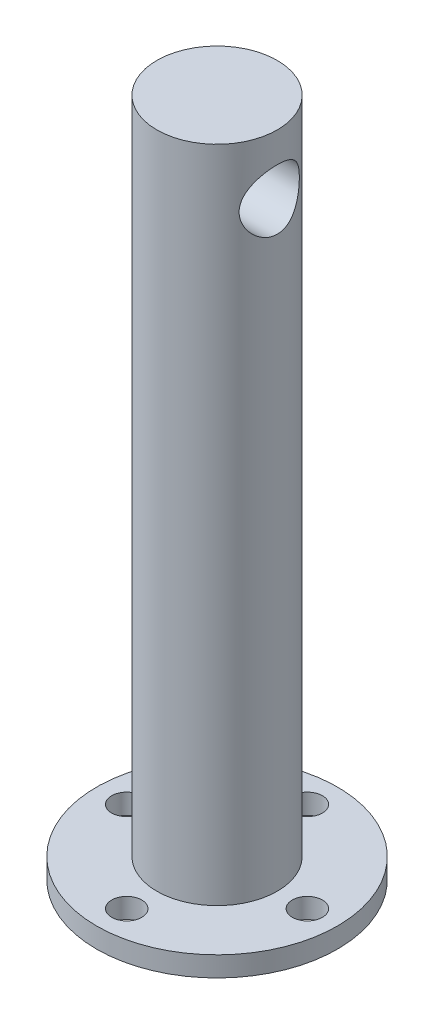
SolidWorks part; units mm, degrees
ref_plane "Front Plane" through (0, 0, 0) normal (0, 0, 1) x (1, 0, 0)
ref_plane "Top Plane" through (0, 0, 0) normal (0, 1, 0) x (1, 0, 0)
ref_plane "Right Plane" through (0, 0, 0) normal (1, 0, 0) x (0, 0, -1)
sketch "Sketch1" plane through (0, 0, 0) normal (0, 1, 0) x (1, 0, 0)
  circle A0 centre (0, 0) radius 30
  dimension "D1" = 60
extrude "Boss-Extrude1" add sketch "Sketch1" along normal blind 5
sketch "Sketch2" plane through (0, 5, 0) normal (0, 1, 0) x (1, 0, 0)
  circle A1 centre (0, 22.5) radius 3.75
  circle A2 centre (22.5, 0) radius 3.75
  circle A3 centre (0, -22.5) radius 3.75
  circle A4 centre (-22.5, 0) radius 3.75
  point P12 (0, 0)
  dimension "D1" = 7.5
  dimension "D2" = 22.5
  dimension "D3" = 4
extrude "Cut-Extrude1" cut sketch "Sketch2" against normal blind 5
sketch "Sketch3" plane through (0, 5, 0) normal (0, 1, 0) x (1, 0, 0)
  circle A0 centre (0, 0) radius 15
  dimension "D1" = 30
extrude "Boss-Extrude2" add sketch "Sketch3" along normal blind 164.27
ref_plane "Plane1" through (15, 0, 0) normal (1, 0, 0) x (0, 0, -1)
sketch "Sketch4" plane through (15, 0, 0) normal (1, 0, 0) x (0, 0, -1)
  line L0 (15, 169.27) -> (-15, 169.27) construction
  line L1 (-15, 169.27) -> (-15, 5) construction
  circle A0 centre (0, 154.27) radius 7.5
  dimension "D1" = 15
  dimension "D2" = 15
  dimension "D3" = 15
extrude "Cut-Extrude2" cut sketch "Sketch4" against normal through all
